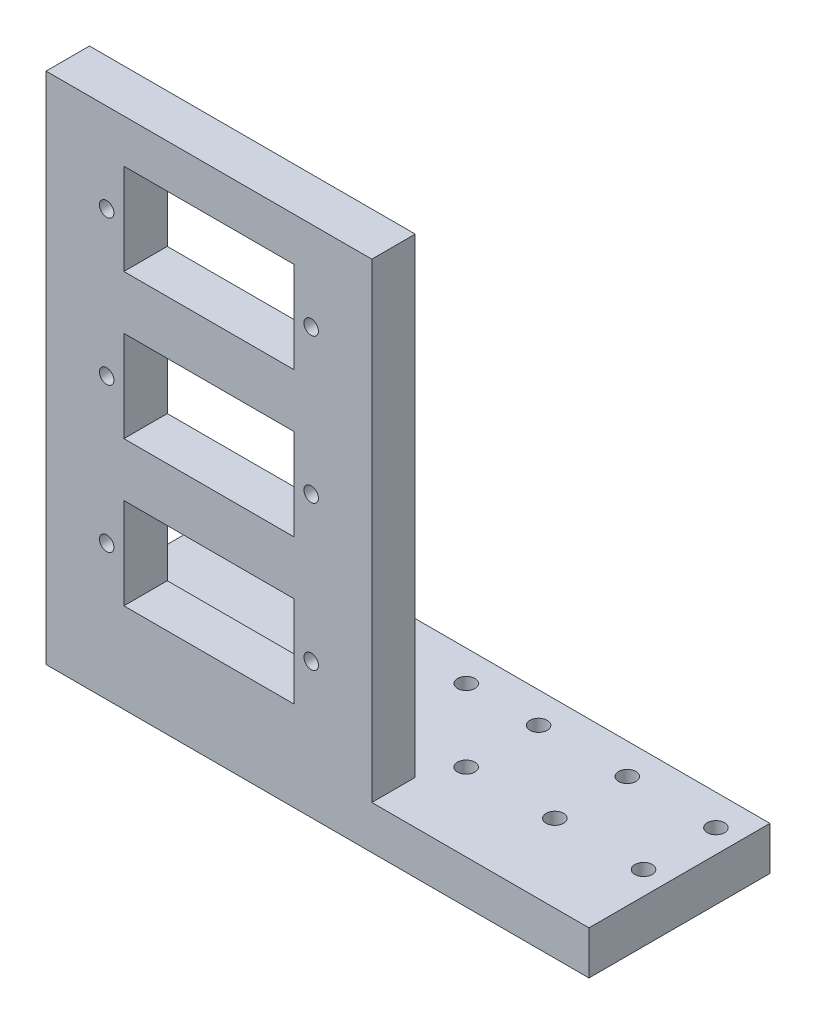
SolidWorks part; units mm, degrees
material "ABS"
ref_plane "Front Plane" through (0, 0, 0) normal (0, 0, 1) x (1, 0, 0)
ref_plane "Top Plane" through (0, 0, 0) normal (0, 1, 0) x (1, 0, 0)
ref_plane "Right Plane" through (0, 0, 0) normal (1, 0, 0) x (0, 0, -1)
sketch "Sketch1" plane through (0, 0, 0) normal (0, 1, 0) x (1, 0, 0)
  line L1 (0, 0) -> (45, 0)
  line L2 (0, 0) -> (0, 6)
  line L3 (0, 6) -> (45, 6)
  line L4 (45, 0) -> (45, 6)
  dimension "D1" = 45
  dimension "D2" = 6
extrude "Boss-Extrude1" add sketch "Sketch1" along normal blind 65
sketch "Sketch2" plane through (0, 0, 0) normal (0, 0, 1) x (1, 0, 0)
  line L0 (22.5, 65) -> (22.5, 59) construction
  line L1 (10.75, 59) -> (34.25, 59)
  line L2 (10.75, 59) -> (10.75, 46.4)
  line L3 (10.75, 46.4) -> (34.25, 46.4)
  line L4 (34.25, 59) -> (34.25, 46.4)
  line L5 (0, 65) -> (45, 65) construction
  line L6 (8.375, 52.7) -> (36.625, 52.7) construction
  line L7 (22.5, 52.7) -> (22.5, 59) construction
  circle A0 centre (8.375, 52.7) radius 1
  circle A1 centre (36.625, 52.7) radius 1
  point P12 (10.75, 52.7)
  dimension "D4" = 2
  dimension "D5" = 28.25
  dimension "D1" = 23.5
  dimension "D2" = 12.6
  dimension "D3" = 6
extrude "Cut-Extrude1" cut sketch "Sketch2" against normal through all
pattern_linear "LPattern1" count 3 spacing 20 along (0, -1, 0) of "Cut-Extrude1"
sketch "Sketch3" plane through (0, 0, 0) normal (0, -1, 0) x (1, 0, 0)
  line L0 (45, 0) -> (45, -6) construction
  line L1 (0, 0) -> (45, 0)
  line L2 (0, 0) -> (0, -25)
  line L3 (0, -25) -> (45, -25)
  line L4 (45, 0) -> (45, -25)
  dimension "D1" = 25
extrude "Boss-Extrude2" add sketch "Sketch3" along normal blind 6
sketch "Sketch4" plane through (45, 0, 0) normal (1, 0, 0) x (0, 0, -1)
  line L1 (25, 0) -> (0, 0)
  line L2 (25, 0) -> (25, -6)
  line L3 (25, -6) -> (0, -6)
  line L4 (0, 0) -> (0, -6)
extrude "Boss-Extrude3" add sketch "Sketch4" along normal blind 30
sketch "Sketch5" plane through (0, -6, 0) normal (0, -1, 0) x (1, 0, 0)
  line L0 (71.7888, -10.7493) -> (47.2888, -10.7493) construction
  circle A0 centre (37.2888, -20.7493) radius 1.2 construction
  circle A1 centre (37.2888, -20.7493) radius 1.2
  circle A2 centre (37.2888, -10.7493) radius 1.2 construction
  circle A3 centre (37.2888, -10.7493) radius 1.2
  circle A4 centre (47.2888, -20.7493) radius 1.2 construction
  circle A5 centre (47.2888, -20.7493) radius 1.2
  circle A6 centre (47.2888, -10.7493) radius 1.2 construction
  circle A7 centre (47.2888, -10.7493) radius 1.2
  circle A8 centre (59.5388, -20.7493) radius 1.2 construction
  circle A9 centre (59.5388, -20.7493) radius 1.2
  circle A10 centre (71.7888, -20.7493) radius 1.2 construction
  circle A11 centre (71.7888, -20.7493) radius 1.2
  circle A12 centre (71.7888, -10.7493) radius 1.2 construction
  circle A13 centre (71.7888, -10.7493) radius 1.2
  circle A14 centre (59.5388, -10.7493) radius 1.2
extrude "Cut-Extrude2" cut sketch "Sketch5" against normal through all
